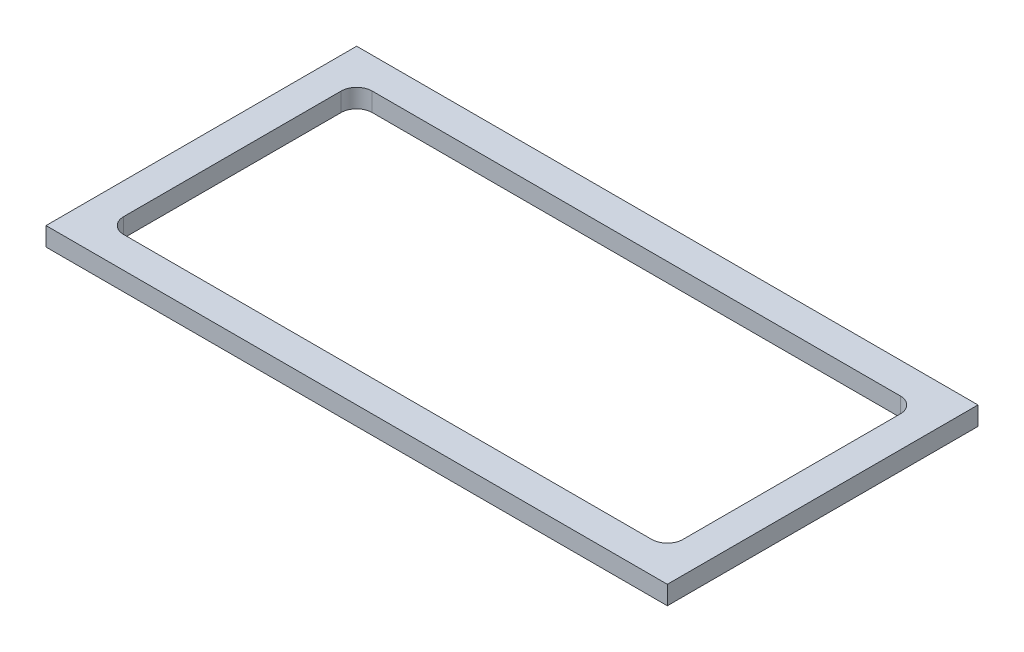
SolidWorks part; units mm, degrees
material "Pine"
ref_plane "Front Plane" through (0, 0, 0) normal (0, 0, 1) x (1, 0, 0)
ref_plane "Top Plane" through (0, 0, 0) normal (0, 1, 0) x (1, 0, 0)
ref_plane "Right Plane" through (0, 0, 0) normal (1, 0, 0) x (0, 0, -1)
sketch "Sketch1" plane through (0, 0, 0) normal (0, 1, 0) x (1, 0, 0)
  line L1 (0, 0) -> (200, 0)
  line L2 (0, 0) -> (0, 100)
  line L3 (0, 100) -> (200, 100)
  line L4 (200, 0) -> (200, 100)
  dimension "D1" = 200
  dimension "D2" = 100
extrude "Boss-Extrude1" add sketch "Sketch1" along normal blind 6
sketch "Sketch2" plane through (0, 6, 0) normal (0, 1, 0) x (1, 0, 0)
  line L0 (0, 100) -> (0, 0) construction
  line L1 (10, 90) -> (190, 90)
  line L2 (10, 90) -> (10, 10)
  line L3 (10, 10) -> (190, 10)
  line L4 (190, 90) -> (190, 10)
  line L5 (200, 0) -> (200, 100) construction
  line L6 (0, 0) -> (200, 0) construction
  line L7 (200, 100) -> (0, 100) construction
  point P6 (200, 50)
  dimension "D1" = 10
  dimension "D2" = 10
  dimension "D3" = 10
  dimension "D4" = 10
extrude "Cut-Extrude1" cut sketch "Sketch2" against normal through all
fillet "Fillet1" radius 5 4 edges at (10, 3, -10) (190, 3, -10) (190, 3, -90) (10, 3, -90)
equation "\"BoardThickness\"= 6"
equation "\"D1@Boss-Extrude1\"=\"BoardThickness\""
equation "\"D2@Sketch2\"=\"D1@Sketch2\""
equation "\"D3@Sketch2\"=\"D1@Sketch2\""
equation "\"D4@Sketch2\"=\"D1@Sketch2\""
